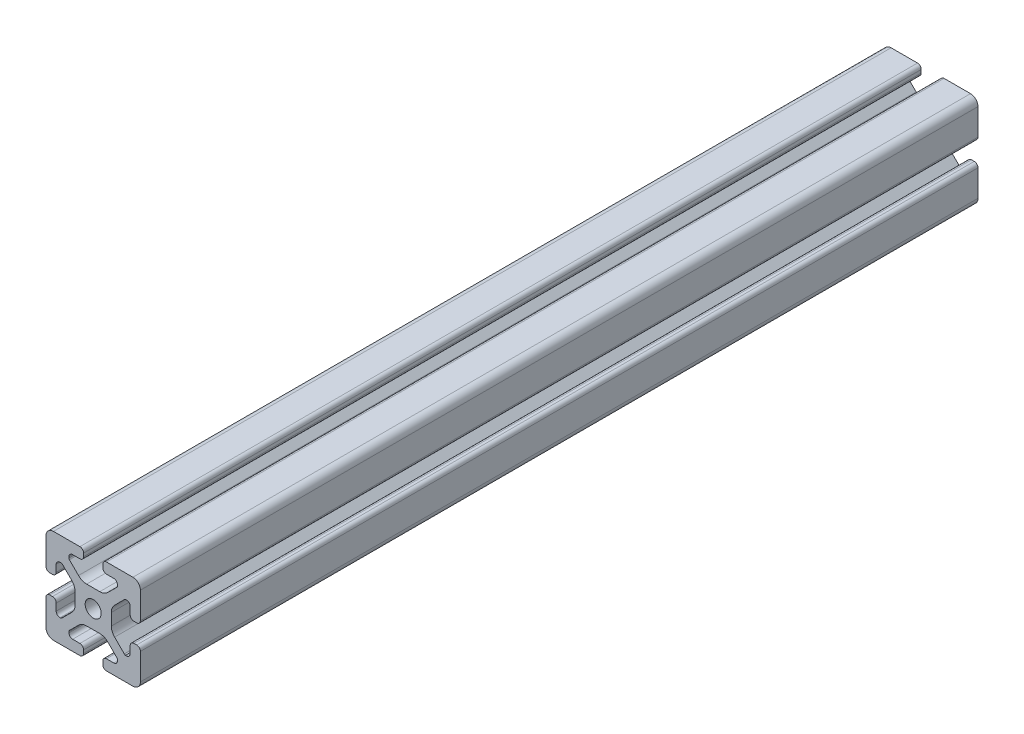
SolidWorks part; units mm, degrees
material "6061 Alloy"
ref_plane "Front Plane" through (0, 0, 0) normal (0, 0, 1) x (1, 0, 0)
ref_plane "Top Plane" through (0, 0, 0) normal (0, 1, 0) x (1, 0, 0)
ref_plane "Right Plane" through (0, 0, 0) normal (1, 0, 0) x (0, 0, -1)
sketch "Sketch1" plane through (0, 0, 0) normal (0, 0, 1) x (1, 0, 0)
  line L0 (0, 19.7407) -> (0, -19.7407) construction
  line L1 (19.0335, 0) -> (-20.7246, 0) construction
  line L2 (-8.715, -15.5246) -> (-5.63, -15.5246)
  line L3 (-10.285, -13.9546) -> (-10.285, -13.4925)
  line L4 (-6.2171, -9.1098) -> (-10.0624, -12.9551)
  line L5 (2.7773, -7.685) -> (-2.7773, -7.685)
  line L6 (10.0624, -12.9551) -> (6.2171, -9.1098)
  line L7 (10.285, -13.9546) -> (10.285, -13.4925)
  line L8 (5.63, -15.5246) -> (8.715, -15.5246)
  line L9 (4.06, -18.43) -> (4.06, -17.0946)
  line L10 (-4.06, -18.43) -> (-4.06, -17.0946)
  line L11 (15.68, -8.7154) -> (15.68, -5.63)
  line L12 (-14.11, -10.2854) -> (-13.8169, -10.2854)
  line L13 (20, -16.83) -> (20, -5.63)
  line L14 (20, 5.63) -> (20, 13.0011)
  line L15 (-16.83, 20) -> (-5.63, 20)
  line L16 (5.63, 20) -> (12.9796, 20)
  line L18 (-8.715, 15.5246) -> (-5.63, 15.5246)
  line L19 (-20, -17.0184) -> (-20, -5.7579)
  line L20 (-20, 5.573) -> (-20, 13.0045)
  line L21 (-15.68, -8.7154) -> (-15.68, -5.7579)
  line L23 (-16.6746, -20) -> (-5.63, -20)
  line L24 (5.63, -20) -> (13, -20)
  line L53 (14.11, -10.2854) -> (13.6201, -10.2854)
  line L54 (13.1637, -9.947) -> (9.0762, -5.8595)
  line L55 (7.685, -2.5008) -> (7.685, 2.5008)
  line L56 (9.0762, 5.8595) -> (13.2795, 10.0628)
  line L57 (13.8169, 10.2854) -> (14.11, 10.2854)
  line L58 (15.68, 8.7154) -> (15.68, 5.63)
  line L59 (17.25, 4.06) -> (18.43, 4.06)
  line L61 (20, 13.0011) -> (20, 16.83)
  line L62 (16.83, 20) -> (12.9796, 20)
  line L64 (4.06, 18.43) -> (4.06, 17.0946)
  line L65 (5.63, 15.5246) -> (8.715, 15.5246)
  line L66 (10.285, 13.9546) -> (10.285, 13.4925)
  line L67 (10.0624, 12.9551) -> (6.2171, 9.1098)
  line L68 (2.7773, 7.685) -> (-2.7773, 7.685)
  line L69 (-6.2171, 9.1098) -> (-10.0624, 12.9551)
  line L70 (-10.285, 13.4925) -> (-10.285, 13.9546)
  line L72 (-4.06, 17.0946) -> (-4.06, 18.43)
  line L75 (-20, 16.83) -> (-20, 13.0045)
  line L77 (-18.43, 4.003) -> (-17.25, 4.003)
  line L78 (-15.68, 5.573) -> (-15.68, 8.4757)
  line L79 (-14.0552, 10.0447) -> (-13.7199, 10.033)
  line L80 (-13.0405, 9.8238) -> (-9.0762, 5.8595)
  line L81 (-7.685, 2.5008) -> (-7.685, -2.5008)
  line L82 (-9.0762, -5.8595) -> (-13.2795, -10.0628)
  line L85 (-17.25, -4.1204) -> (-18.43, -4.1204)
  line L100 (13, -20) -> (16.83, -20)
  line L103 (18.43, -4.06) -> (17.25, -4.06)
  arc A0 (-5.63, -15.5246) -> (-4.06, -17.0946) centre (-5.63, -17.0946) cw
  arc A1 (-8.715, -15.5246) -> (-10.285, -13.9546) centre (-8.715, -13.9546) cw
  arc A2 (-10.285, -13.4925) -> (-10.0624, -12.9551) centre (-9.525, -13.4925) cw
  arc A3 (-6.2171, -9.1098) -> (-2.7773, -7.685) centre (-2.7773, -12.5496) cw
  arc A4 (2.7773, -7.685) -> (6.2171, -9.1098) centre (2.7773, -12.5496) cw
  arc A5 (10.0624, -12.9551) -> (10.285, -13.4925) centre (9.525, -13.4925) cw
  arc A6 (10.285, -13.9546) -> (8.715, -15.5246) centre (8.715, -13.9546) cw
  arc A7 (4.06, -17.0946) -> (5.63, -15.5246) centre (5.63, -17.0946) cw
  arc A8 (5.63, -20) -> (4.06, -18.43) centre (5.63, -18.43) cw
  arc A9 (-4.06, -18.43) -> (-5.63, -20) centre (-5.63, -18.43) cw
  circle A45 centre (0, 0) radius 3.4
  arc A46 (17.25, -4.06) -> (15.68, -5.63) centre (17.25, -5.63) ccw
  arc A47 (14.11, -10.2854) -> (15.68, -8.7154) centre (14.11, -8.7154) ccw
  arc A48 (13.1637, -9.947) -> (13.6201, -10.2854) centre (13.8117, -9.55) ccw
  arc A49 (7.685, -2.5008) -> (9.0762, -5.8595) centre (12.435, -2.5008) ccw
  arc A50 (9.0762, 5.8595) -> (7.685, 2.5008) centre (12.435, 2.5008) ccw
  arc A51 (13.8169, 10.2854) -> (13.2795, 10.0628) centre (13.8169, 9.5254) ccw
  arc A52 (15.68, 8.7154) -> (14.11, 10.2854) centre (14.11, 8.7154) ccw
  arc A53 (15.68, 5.63) -> (17.25, 4.06) centre (17.25, 5.63) ccw
  arc A54 (18.43, 4.06) -> (20, 5.63) centre (18.43, 5.63) ccw
  arc A55 (20, 16.83) -> (16.83, 20) centre (16.83, 16.83) ccw
  arc A56 (5.63, 20) -> (4.06, 18.43) centre (5.63, 18.43) ccw
  arc A57 (4.06, 17.0946) -> (5.63, 15.5246) centre (5.63, 17.0946) ccw
  arc A58 (10.285, 13.9546) -> (8.715, 15.5246) centre (8.715, 13.9546) ccw
  arc A59 (10.0624, 12.9551) -> (10.285, 13.4925) centre (9.525, 13.4925) ccw
  arc A60 (2.7773, 7.685) -> (6.2171, 9.1098) centre (2.7773, 12.5496) ccw
  arc A61 (-6.2171, 9.1098) -> (-2.7773, 7.685) centre (-2.7773, 12.5496) ccw
  arc A62 (-10.285, 13.4925) -> (-10.0624, 12.9551) centre (-9.525, 13.4925) ccw
  arc A63 (-8.715, 15.5246) -> (-10.285, 13.9546) centre (-8.715, 13.9546) ccw
  arc A64 (-5.63, 15.5246) -> (-4.06, 17.0946) centre (-5.63, 17.0946) ccw
  arc A65 (-4.06, 18.43) -> (-5.63, 20) centre (-5.63, 18.43) ccw
  arc A66 (-16.83, 20) -> (-20, 16.83) centre (-16.83, 16.83) ccw
  arc A67 (-20, 5.573) -> (-18.43, 4.003) centre (-18.43, 5.573) ccw
  arc A68 (-17.25, 4.003) -> (-15.68, 5.573) centre (-17.25, 5.573) ccw
  arc A69 (-14.0552, 10.0447) -> (-15.68, 8.4757) centre (-14.11, 8.4757) ccw
  arc A70 (-13.0405, 9.8238) -> (-13.7199, 10.033) centre (-13.5779, 9.2864) ccw
  arc A71 (-7.685, 2.5008) -> (-9.0762, 5.8595) centre (-12.435, 2.5008) ccw
  arc A72 (-9.0762, -5.8595) -> (-7.685, -2.5008) centre (-12.435, -2.5008) ccw
  arc A73 (-13.8169, -10.2854) -> (-13.2795, -10.0628) centre (-13.8169, -9.5254) ccw
  arc A74 (-15.68, -8.7154) -> (-14.11, -10.2854) centre (-14.11, -8.7154) ccw
  arc A75 (-15.68, -5.7579) -> (-17.25, -4.1204) centre (-17.2485, -5.6904) ccw
  arc A76 (-18.43, -4.1204) -> (-20, -5.7579) centre (-18.4315, -5.6904) ccw
  arc A77 (-20, -17.0184) -> (-16.6746, -20) centre (-16.8354, -16.8341) ccw
  arc A88 (16.83, -20) -> (20, -16.83) centre (16.83, -16.83) ccw
  arc A89 (20, -5.63) -> (18.43, -4.06) centre (18.43, -5.63) ccw
  dimension "D2" = 6.8
  dimension "D7" = 20.57
  dimension "D1" = 40
  dimension "D3" = 4.32
  dimension "D4" = 15.37
  dimension "D5" = 20
  dimension "D6" = 4.32
  dimension "D9" = 15.37
extrude "Extrude1" add sketch "Sketch1" against normal blind 355
